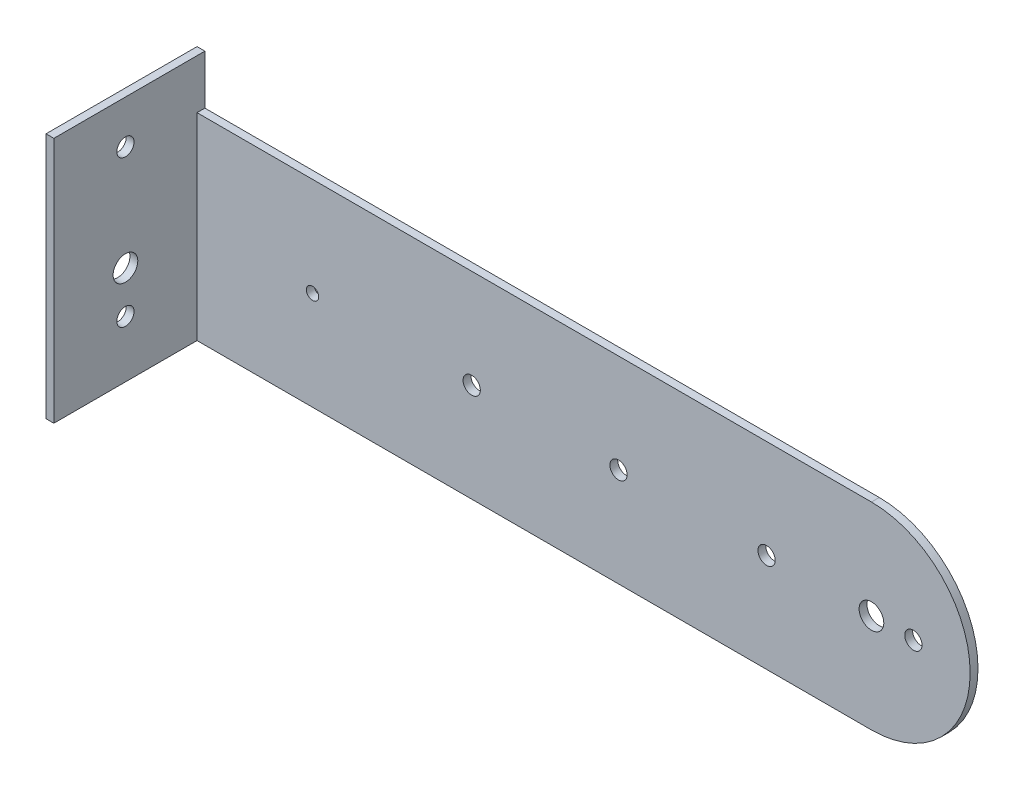
SolidWorks part; units mm, degrees
ref_plane "Front Plane" through (0, 0, 0) normal (0, 0, 1) x (1, 0, 0)
ref_plane "Top Plane" through (0, 0, 0) normal (0, 1, 0) x (1, 0, 0)
ref_plane "Right Plane" through (0, 0, 0) normal (1, 0, 0) x (0, 0, -1)
sketch "Sketch1" plane through (0, 0, 0) normal (0, 0, 1) x (1, 0, 0)
  line L0 (-38.514, 20) -> (38.514, 20)
  line L1 (-38.514, -20) -> (38.514, -20)
  line L2 (-38.514, 20) -> (-99.73, 20)
  line L3 (-99.73, 20) -> (-99.73, -20)
  line L4 (-99.73, -20) -> (-38.514, -20)
  arc A1 (38.514, -20) -> (38.514, 20) centre (38.514, 0) ccw
  point P8 (0, 20)
  point P9 (0, -20)
  dimension "D1" = 99.73
  dimension "D2" = 138.244
  dimension "D3" = 40
extrude "Boss-Extrude1" add sketch "Sketch1" along normal blind 1.59
sketch "Sketch2" plane through (0, 0, 1.59) normal (0, 0, 1) x (1, 0, 0)
  circle A0 centre (38.514, 0) radius 2.5
  arc A1 (38.514, -20) -> (38.514, 20) centre (38.514, 0) ccw construction
  circle A2 centre (47.014, 0) radius 1.75
  circle A3 centre (17.264, 0) radius 1.75
  circle A4 centre (-12.736, 0) radius 1.75
  circle A5 centre (-42.486, 0) radius 1.75
  point P9 (0, 0)
  dimension "D1" = 5
  dimension "D4" = 3.5
  dimension "D5" = 29.75
  dimension "D6" = 3.5
  dimension "D2" = 8.5
  dimension "D3" = 29.75
  dimension "D7" = 30
extrude "Cut-Extrude2" cut sketch "Sketch2" against normal blind 1.59
sketch "Sketch3" plane through (0, 0, 1.59) normal (0, 0, 1) x (1, 0, 0)
  line L0 (38.514, 20) -> (-99.73, 20) construction
  line L1 (-98.14, 20) -> (-99.73, 20)
  line L2 (-98.14, 20) -> (-98.14, -20)
  line L3 (-98.14, -20) -> (-99.73, -20)
  line L4 (-99.73, 20) -> (-99.73, -20)
  dimension "D1" = 1.59
extrude "Boss-Extrude2" add sketch "Sketch3" along normal blind 30.602
sketch "Sketch4" plane through (-99.73, 0, 0) normal (-1, 0, 0) x (0, 0, 1)
  line L0 (0, 0) -> (32.192, 0) construction
  line L1 (32.192, 20) -> (32.192, -20) construction
  line L2 (16.096, 20) -> (16.096, -20) construction
  line L3 (32.192, 20) -> (0, 20) construction
  line L4 (32.192, -20) -> (0, -20) construction
  circle A0 centre (16.096, 0) radius 7.5 construction
  circle A1 centre (16.096, 7.5) radius 0.75
  circle A2 centre (8.596, 0) radius 0.75
  circle A3 centre (23.596, 0) radius 0.75
  circle A4 centre (16.096, -7.5) radius 0.75
  dimension "D1" = 15
  dimension "D2" = 1.5
  dimension "D3" = 1.5
extrude "Cut-Extrude3" [suppressed] cut sketch "Sketch4" against normal blind 40
sketch "Sketch5" plane through (-99.73, 0, 0) normal (-1, 0, 0) x (0, 0, 1)
  line L0 (32.192, -20) -> (0, -20) construction
  line L1 (32.192, 20) -> (30.602, 20)
  line L2 (32.192, 20) -> (32.192, -20)
  line L3 (32.192, -20) -> (30.602, -20)
  line L4 (30.602, 20) -> (30.602, -20)
  dimension "D1" = 1.59
extrude "Cut-Extrude4" cut sketch "Sketch5" against normal blind 10
sketch "Sketch6" [suppressed] plane through (-99.73, 0, 0) normal (-1, 0, 0) x (0, 0, 1)
  line L1 (0, -20) -> (40, -20)
  line L2 (0, -20) -> (0, -30)
  line L3 (0, -30) -> (40, -30)
  line L4 (40, -20) -> (40, -30)
  point P5 (0, 0)
  dimension "D1" = 10
extrude "Boss-Extrude3" [suppressed] add sketch "Sketch6" against normal up to surface (1.59 mm away)
sketch "Sketch8" plane through (-99.73, 0, 0) normal (-1, 0, 0) x (0, 0, 1)
  line L0 (20.8, 20) -> (20.8, -20) construction
  line L1 (30.602, 20) -> (0, 20) construction
  circle A0 centre (20.8, 0) radius 2.5
  circle A1 centre (20.8, 8.5) radius 1.75
  circle A2 centre (20.8, -21.25) radius 1.75
  point P11 (0, 0)
  dimension "D2" = 5
  dimension "D3" = 3.5
  dimension "D4" = 3.5
  dimension "D1" = 20.8
  dimension "D5" = 8.5
  dimension "D6" = 29.75
extrude "Cut-Extrude5" [suppressed] cut sketch "Sketch8" against normal blind 10
sketch "Sketch9" plane through (-99.73, 0, 0) normal (-1, 0, 0) x (0, 0, 1)
  line L1 (0, 20) -> (30.602, 20)
  line L2 (0, 20) -> (0, 30)
  line L3 (0, 30) -> (30.602, 30)
  line L4 (30.602, 20) -> (30.602, 30)
  point P5 (15.301, 20)
  point P6 (0, 0)
  dimension "D1" = 10
extrude "Boss-Extrude4" add sketch "Sketch9" against normal up to surface (1.59 mm away) up to face at (-98.14, 0, 16.096)
sketch "Sketch10" plane through (-99.73, 0, 0) normal (-1, 0, 0) x (0, 0, 1)
  line L0 (16.096, 26.6396) -> (16.096, -4.3358) construction
  circle A0 centre (16.096, -8.5) radius 1.75
  circle A1 centre (16.096, 0) radius 2.5
  circle A2 centre (16.096, 21.25) radius 1.75
  point P9 (0, 0)
  point P10 (0, 0)
  dimension "D4" = 3.5
  dimension "D5" = 5
  dimension "D6" = 3.5
  dimension "D1" = 16.096
  dimension "D2" = 8.5
  dimension "D3" = 29.75
extrude "Cut-Extrude6" cut sketch "Sketch10" against normal blind 10
sketch "Sketch11" plane through (0, 0, 1.59) normal (0, 0, 1) x (1, 0, 0)
  line L0 (-98.14, -20) -> (-98.14, 20) construction
  circle A0 centre (-74.73, 0) radius 1.25
  point P2 (0, 0)
  dimension "D2" = 2.5
  dimension "D1" = 23.41
extrude "Cut-Extrude7" cut sketch "Sketch11" against normal blind 10
